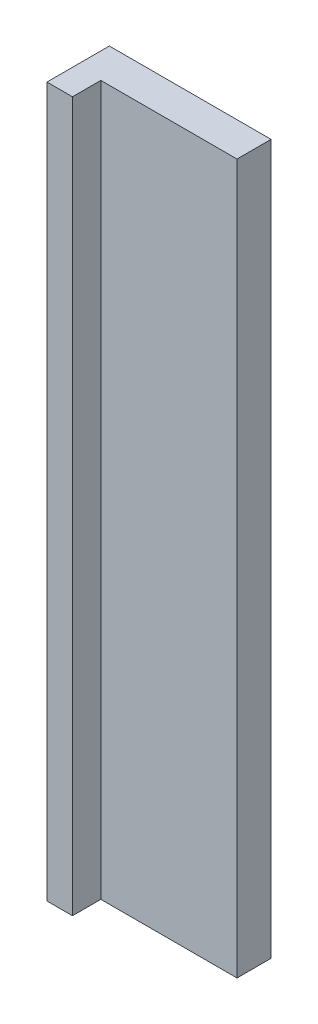
SolidWorks part; units mm, degrees
ref_plane "Alzado" through (0, 0, 0) normal (0, 0, 1) x (1, 0, 0)
ref_plane "Planta" through (0, 0, 0) normal (0, 1, 0) x (1, 0, 0)
ref_plane "Vista lateral" through (0, 0, 0) normal (1, 0, 0) x (0, 0, -1)
sketch "Croquis1" plane through (0, 0, 0) normal (0, 0, 1) x (1, 0, 0)
  line L1 (0, 0) -> (28.5, 0)
  line L2 (0, 0) -> (0, 125)
  line L3 (0, 125) -> (28.5, 125)
  line L4 (28.5, 0) -> (28.5, 125)
  dimension "D1" = 125
  dimension "D2" = 28.5
extrude "Saliente-Extruir1" add sketch "Croquis1" along normal blind 6
sketch "Croquis2" plane through (0, 0, 6) normal (0, 0, 1) x (1, 0, 0)
  line L0 (28.5, 125) -> (0, 125) construction
  line L1 (0, 0) -> (4.5, 0)
  line L2 (0, 0) -> (0, 125)
  line L3 (0, 125) -> (4.5, 125)
  line L4 (4.5, 0) -> (4.5, 125)
  dimension "D1" = 4.5
extrude "Saliente-Extruir2" add sketch "Croquis2" along normal blind 5
